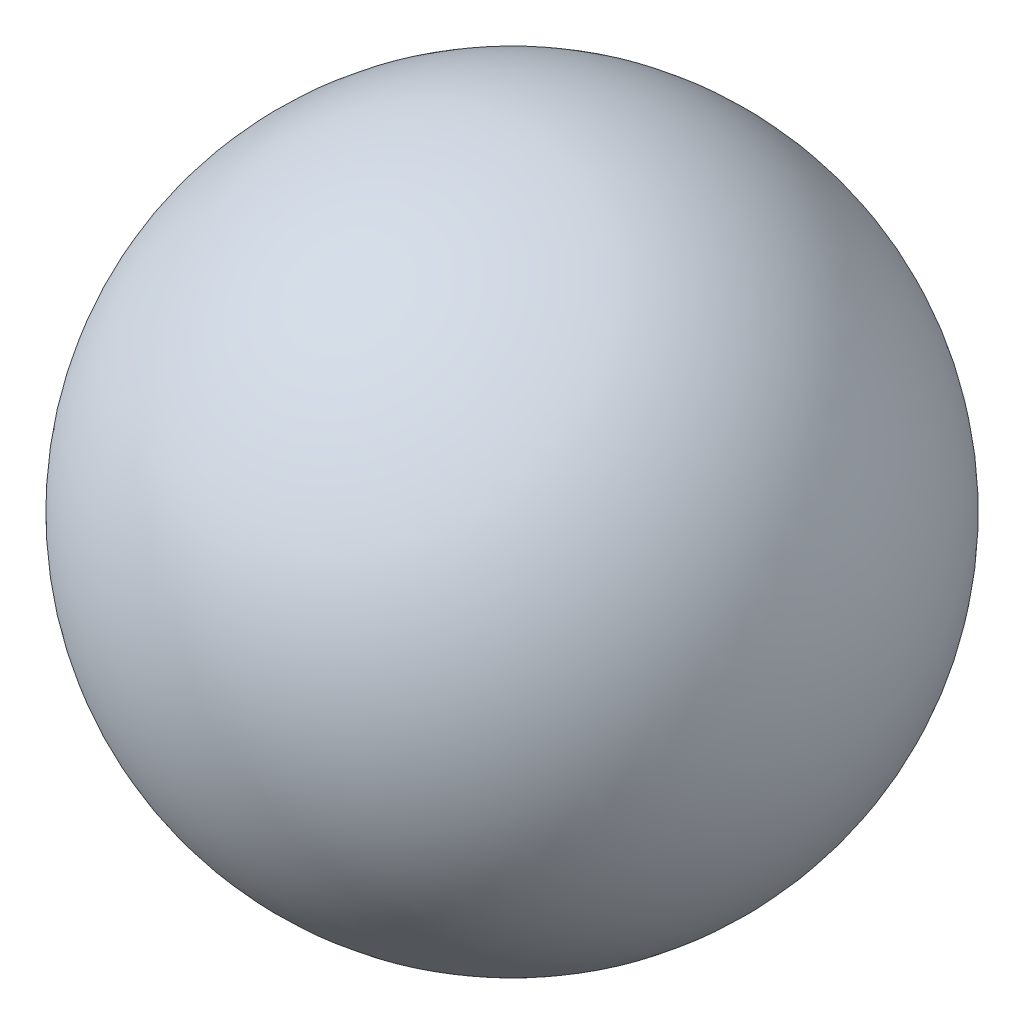
SolidWorks part; units mm, degrees
material "1023 Carbon Steel Sheet (SS)"
ref_plane "Front Plane" through (0, 0, 0) normal (0, 0, 1) x (1, 0, 0)
ref_plane "Top Plane" through (0, 0, 0) normal (0, 1, 0) x (1, 0, 0)
ref_plane "Right Plane" through (0, 0, 0) normal (1, 0, 0) x (0, 0, -1)
sketch "Sketch1" plane through (0, 0, 0) normal (0, 0, 1) x (1, 0, 0)
  line L0 (0, 40) -> (0, -40)
  arc A0 (0, -40) -> (0, 40) centre (0, 0) ccw
  dimension "D1" = 80
revolve "Revolve1" add sketch "Sketch1" angle 360 about L0
